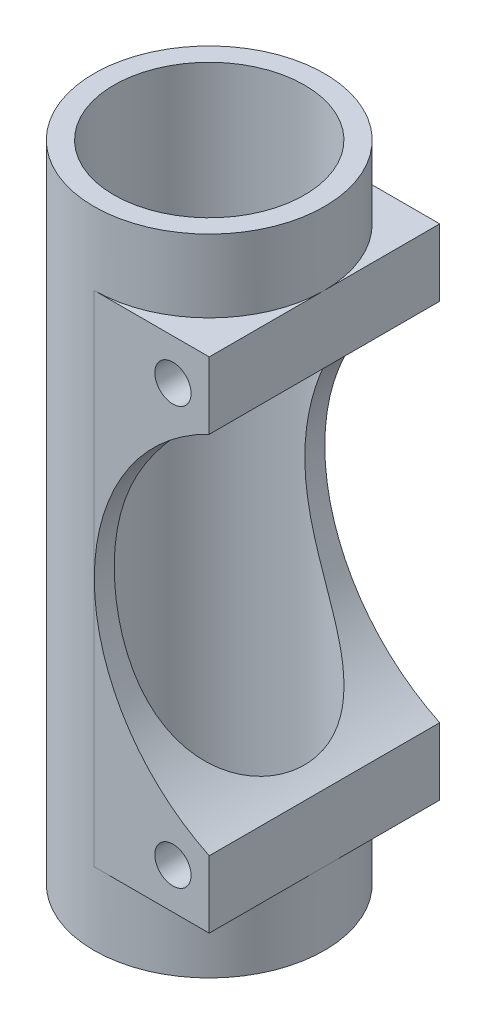
SolidWorks part; units mm, degrees
material "6061-T6 (SS)"
ref_plane "Front Plane" through (0, 0, 0) normal (0, 0, 1) x (1, 0, 0)
ref_plane "Top Plane" through (0, 0, 0) normal (0, 1, 0) x (1, 0, 0)
ref_plane "Right Plane" through (0, 0, 0) normal (1, 0, 0) x (0, 0, -1)
sketch "Sketch1" plane through (0, 0, 0) normal (0, 1, 0) x (1, 0, 0)
  circle A0 centre (0, 0) radius 10.5
  circle A1 centre (0, 0) radius 12.7
  dimension "D1" = 21
  dimension "D2" = 25.4
extrude "Boss-Extrude1" add sketch "Sketch1" along normal blind 71
sketch "Sketch2" plane through (0, 0, 0) normal (0, -1, 0) x (1, 0, 0)
  line L0 (0, 12.7) -> (12.7, 12.7)
  line L1 (12.7, 12.7) -> (12.7, -12.7)
  line L2 (12.7, -12.7) -> (0, -12.7)
  arc A0 (0, -12.7) -> (0, 12.7) centre (0, 0) ccw
  circle M1 centre (0, 0) radius 12.7
extrude "Boss-Extrude2" add sketch "Sketch2" against normal blind 63 contours L1 L0 M1 | L2 L1 M1
sketch "Sketch3" plane through (0, 0, 0) normal (0, -1, 0) x (1, 0, 0)
  line L0 (0, 12.7) -> (12.7, 12.7)
  line L1 (12.7, 12.7) -> (12.7, -12.7) construction
  line L2 (0, 12.7) -> (12.7, 12.7) construction
  line L3 (12.7, 12.7) -> (12.7, -12.7)
  line L4 (12.7, -12.7) -> (0, -12.7)
  arc A0 (0, -12.7) -> (0, 12.7) centre (0, 0) ccw
  line M2 (0, -12.7) -> (12.7, -12.7)
  line M3 (12.7, -12.7) -> (12.7, 12.7)
  line M4 (12.7, 12.7) -> (0, 12.7)
extrude "Cut-Extrude1" cut sketch "Sketch3" against normal blind 8 contours A0 L3 M4 | A0 M2 M3
sketch "Sketch4" plane through (0, 0, 0) normal (0, 0, 1) x (1, 0, 0)
  line L3 (12.7, 63) -> (12.7, 8) construction
  line L5 (10.4999, 35.5) -> (10.4999, 54.4) construction
  line L6 (10.4999, 35.5) -> (10.4999, 16.6) construction
  circle A3 centre (22.3312, 35.5) radius 22.2977
extrude "Cut-Extrude2" cut sketch "Sketch4" against normal blind 16 and the other way blind 15
sketch "Sketch5" plane through (0, 0, -12.7) normal (0, 0, -1) x (-1, 0, 0)
  line L0 (-12.7, 63) -> (-8.7, 63) construction
  line L1 (0, 63) -> (-12.7, 63) construction
  line L2 (-8.7, 63) -> (-8.7, 58.5) construction
  line L3 (-12.7, 8) -> (-8.7, 8) construction
  line L4 (-12.7, 8) -> (0, 8) construction
  line L5 (-8.7, 8) -> (-8.7, 12.5) construction
  circle A0 centre (-8.7, 58.5) radius 2
  circle A1 centre (-8.7, 12.5) radius 2
  dimension "D1" = 4.5
  dimension "D2" = 4
  dimension "D3" = 4
  dimension "D4" = 4.5
  dimension "D5" = 4
  dimension "D6" = 4
extrude "Cut-Extrude3" cut sketch "Sketch5" against normal blind 4
sketch "Sketch6" plane through (0, 0, 12.7) normal (0, 0, 1) x (1, 0, 0)
  line L0 (12.7, 63) -> (8.7, 63) construction
  line L1 (12.7, 63) -> (0, 63) construction
  line L2 (8.7, 63) -> (8.7, 58.5) construction
  line L3 (12.7, 8) -> (8.7, 8) construction
  line L4 (12.7, 8) -> (0, 8) construction
  line L5 (8.7, 8) -> (8.7, 12.5) construction
  circle A0 centre (8.7, 58.5) radius 2
  circle A1 centre (8.7, 12.5) radius 2
  dimension "D1" = 4
  dimension "D3" = 4
  dimension "D2" = 4.5
  dimension "D4" = 4.5
extrude "Cut-Extrude4" cut sketch "Sketch6" against normal blind 4
